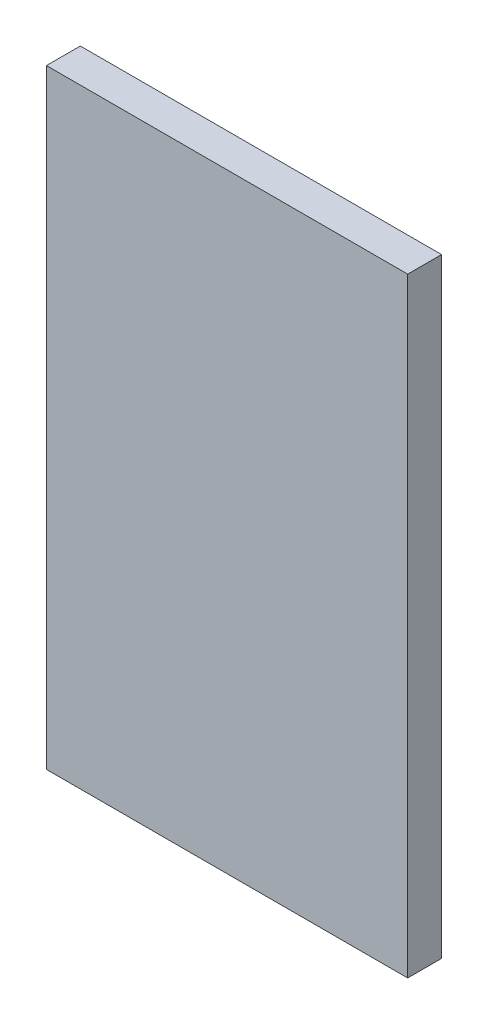
SolidWorks part; units mm, degrees
ref_plane "Front" through (0, 0, 0) normal (0, 0, 1) x (1, 0, 0)
ref_plane "Top" through (0, 0, 0) normal (0, 1, 0) x (1, 0, 0)
ref_plane "Right" through (0, 0, 0) normal (1, 0, 0) x (0, 0, -1)
sketch "Sketch1" plane through (0, 0, 0) normal (0, 0, 1) x (1, 0, 0)
  line L1 (-101.6, 171.45) -> (101.6, 171.45)
  line L2 (-101.6, 171.45) -> (-101.6, -171.45)
  line L3 (-101.6, -171.45) -> (101.6, -171.45)
  line L4 (101.6, 171.45) -> (101.6, -171.45)
  line L5 (-101.6, 171.45) -> (101.6, -171.45) construction
  line L6 (-101.6, -171.45) -> (101.6, 171.45) construction
  point P0 (0, 0)
  dimension "D1" = 342.9
  dimension "D2" = 203.2
extrude "Boss-Extrude1" add sketch "Sketch1" along normal blind 19.05
